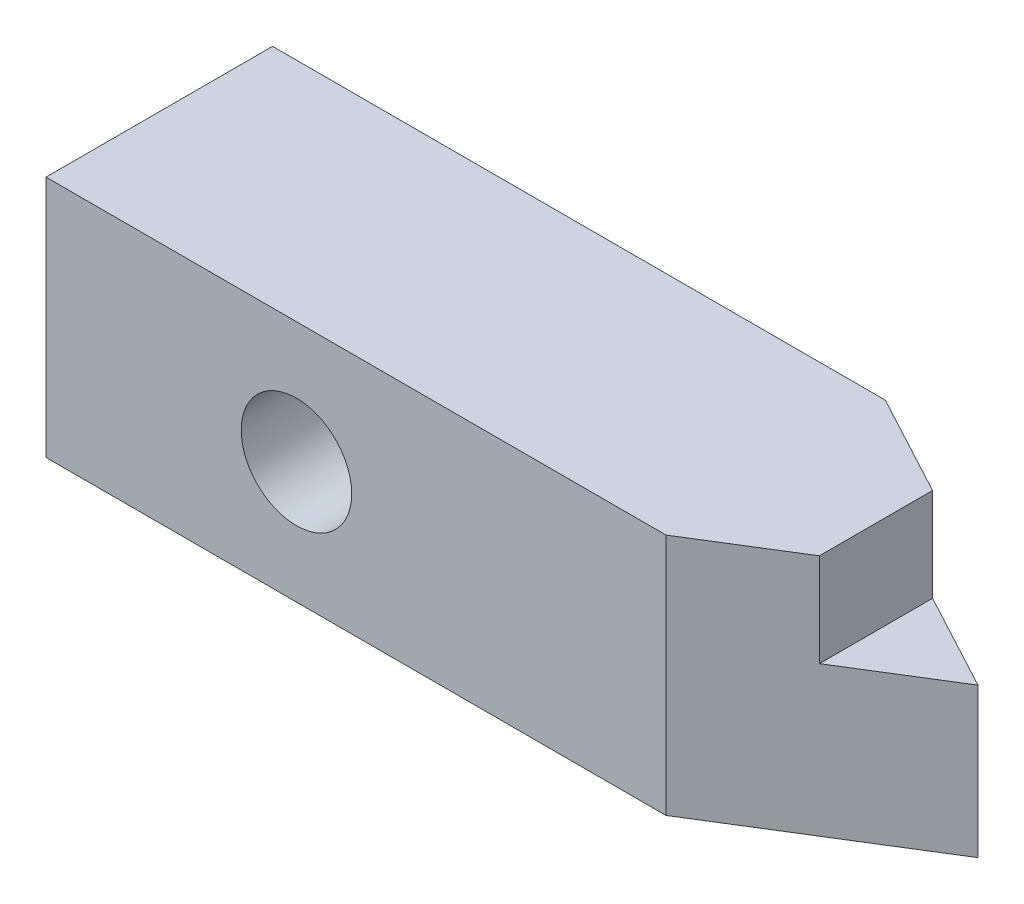
SolidWorks part; units mm, degrees
ref_plane "정면" through (0, 0, 0) normal (0, 0, 1) x (1, 0, 0)
ref_plane "윗면" through (0, 0, 0) normal (0, 1, 0) x (1, 0, 0)
ref_plane "우측면" through (0, 0, 0) normal (1, 0, 0) x (0, 0, -1)
sketch "스케치2" plane through (0, 0, 0) normal (0, 1, 0) x (1, 0, 0)
  line L0 (-30.1456, 0) -> (-30.1456, 24.253)
  line L1 (-30.1456, 24.253) -> (35.4677, 24.253)
  line L2 (35.4677, 24.253) -> (56.8544, 12.7898)
  line L3 (56.8544, 12.7898) -> (36.2336, 0)
  line L4 (36.2336, 0) -> (-30.1456, 0)
  dimension "D1" = 87
  dimension "D2" = 60
extrude "보스-돌출1" add sketch "스케치2" along normal blind 26
sketch "스케치3" plane through (0, 0, 0) normal (0, 0, 1) x (1, 0, 0)
  line L0 (-30.1456, 26) -> (-30.1456, 0) construction
  line L1 (46.3729, 29.5959) -> (70.7396, 29.5959)
  line L2 (46.3729, 29.5959) -> (46.3729, 16)
  line L3 (46.3729, 16) -> (70.7396, 16)
  line L4 (70.7396, 29.5959) -> (70.7396, 16)
  line L5 (36.2336, 0) -> (56.8544, 0) construction
  line L6 (56.8544, 26) -> (56.8544, 0) construction
  circle A0 centre (-3.3314, 13) radius 5.9157
  point P8 (-30.1456, 13)
  dimension "D1" = 16
  dimension "D2" = 10.4815
extrude "컷-돌출2" cut sketch "스케치3" against normal blind 46
sketch "스케치6" plane through (0, 0, 0) normal (0, -1, 0) x (1, 0, 0)
  line L0 (-30.1456, 18.5398) -> (-30.1456, -38.921)
  line L1 (-30.1456, -38.921) -> (-58.9509, -38.921)
  line L2 (-58.9509, -38.921) -> (-58.9509, -20.3811)
  line L3 (-58.9509, -20.3811) -> (-42.4416, -20.3811)
  line L4 (-42.4416, -20.3811) -> (-42.4416, 0)
  line L5 (-42.4416, 0) -> (-58.9509, 0)
  line L6 (-58.9509, 0) -> (-58.9509, 18.5398)
  line L7 (-58.9509, 18.5398) -> (-30.1456, 18.5398)
